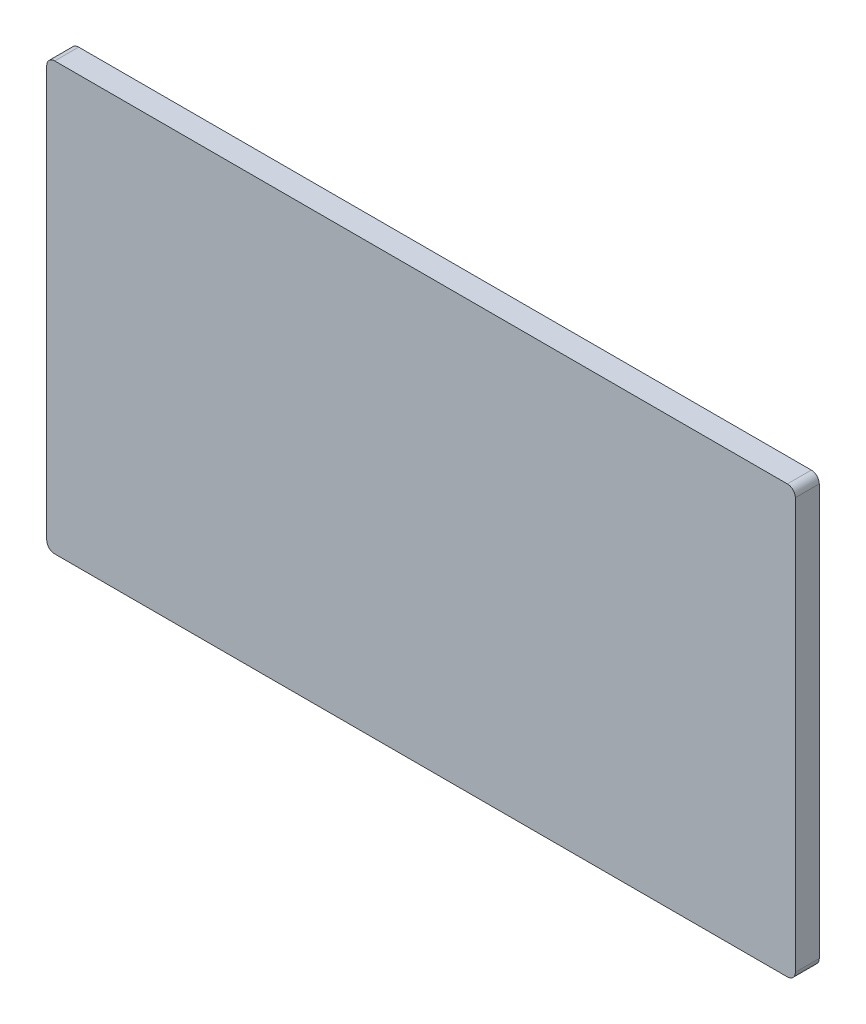
SolidWorks part; units mm, degrees
ref_plane "Front Plane" through (0, 0, 0) normal (0, 0, 1) x (1, 0, 0)
ref_plane "Top Plane" through (0, 0, 0) normal (0, 1, 0) x (1, 0, 0)
ref_plane "Right Plane" through (0, 0, 0) normal (1, 0, 0) x (0, 0, -1)
sketch "Sketch1" plane through (0, 0, 0) normal (0, 0, 1) x (1, 0, 0)
  line L1 (-46.9, 26.75) -> (46.9, 26.75)
  line L2 (-46.9, 26.75) -> (-46.9, -26.75)
  line L3 (-46.9, -26.75) -> (46.9, -26.75)
  line L4 (46.9, 26.75) -> (46.9, -26.75)
  line L5 (-46.9, 26.75) -> (46.9, -26.75) construction
  line L6 (-46.9, -26.75) -> (46.9, 26.75) construction
  point P0 (0, 0)
  dimension "D1" = 53.5
  dimension "D2" = 93.8
extrude "Boss-Extrude1" add sketch "Sketch1" along normal blind 3
fillet "Fillet1" radius 1 4 edges at (-46.9, -26.75, 1.5) (46.9, -26.75, 1.5) (46.9, 26.75, 1.5) (-46.9, 26.75, 1.5)
